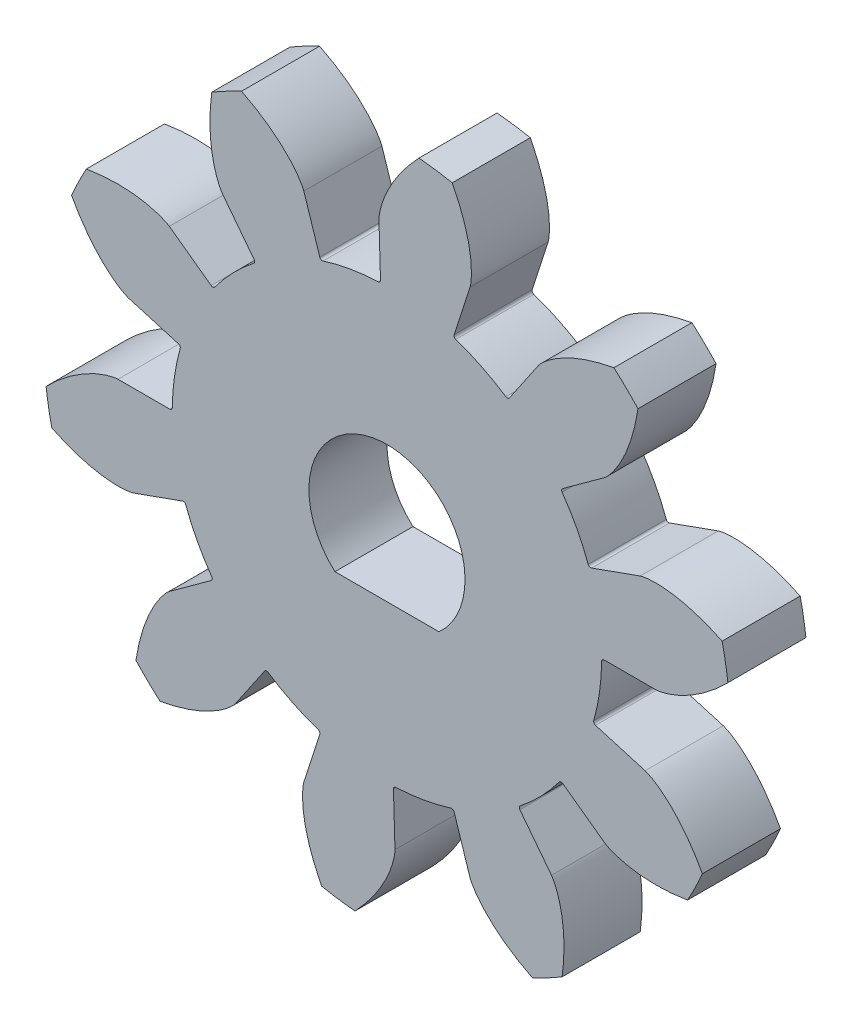
SolidWorks part; units mm, degrees
ref_plane "Front Plane" through (0, 0, 0) normal (0, 0, 1) x (1, 0, 0)
ref_plane "Top Plane" through (0, 0, 0) normal (0, 1, 0) x (1, 0, 0)
ref_plane "Right Plane" through (0, 0, 0) normal (1, 0, 0) x (0, 0, -1)
sketch "Sketch1" plane through (0, 0, 0) normal (0, 0, 1) x (1, 0, 0)
  line L0 (-2, -2.2361) -> (2, -2.2361)
  circle A0 centre (0, 0) radius 13.2013
  arc A1 (2, -2.2361) -> (-2, -2.2361) centre (0, 0) ccw
  dimension "D1" = 26.4026
  dimension "D2" = 6
  dimension "D3" = 4
extrude "Boss-Extrude1" add sketch "Sketch1" along normal blind 3
sketch "Sketch3" plane through (0, 0, 0) normal (0, 0, 1) x (1, 0, 0)
  line L0 (8.2508, 0) -> (10.3377, 0)
  line L1 (9.9225, -2.9001) -> (7.9195, -2.3146)
  line L3 (0, 0) -> (-13.0681, 1.8706) construction
  circle A0 centre (0, 0) radius 11.0011 construction
  circle A1 centre (0, 0) radius 10.3377 construction
  arc A2 (7.9195, -2.3146) -> (8.2508, 0) centre (0, 0) ccw
  circle A3 centre (0, 0) radius 13.2013 construction
  spline S0 degree 4 poles (10.3377, 0) (10.3425, 0.0001) (10.3563, 0.0006) (10.3822, 0.0025) (10.4243, 0.0071) (10.4778, 0.0151) (10.5468, 0.0278) (10.6275, 0.0458) (10.7158, 0.0688) (10.8111, 0.0974) (10.9056, 0.1289) (10.9991, 0.1631) (11.0917, 0.1997) (11.203, 0.247) (11.3352, 0.3079) (11.4879, 0.3849) (11.6587, 0.4791) (11.8299, 0.5825) (11.996, 0.6901) (12.1609, 0.8055) (12.3183, 0.9219) (12.4785, 1.0495) (12.6247, 1.1707) (12.7846, 1.3138) (12.9125, 1.4313) (13.0769, 1.5939) (13.1726, 1.6921) (13.2831, 1.8096) (13.3313, 1.8632) (13.361, 1.8961) knots 0 0 0 0 0 0.005377 0.015084 0.028532 0.04661 0.064855 0.092111 0.119476 0.146842 0.174209 0.201575 0.228941 0.256307 0.307035 0.361767 0.4165 0.471232 0.525964 0.580697 0.635429 0.690161 0.744894 0.799626 0.854358 0.909091 0.954545 1 1 1 1 1 construction
  spline S1 degree 4 poles (10.3377, 0) (10.3425, 0.0001) (10.3563, 0.0006) (10.3822, 0.0025) (10.4243, 0.0071) (10.4778, 0.0151) (10.5468, 0.0278) (10.6275, 0.0458) (10.7158, 0.0688) (10.8111, 0.0974) (10.9056, 0.1289) (10.9991, 0.1631) (11.0917, 0.1997) (11.203, 0.247) (11.3352, 0.3079) (11.4879, 0.3849) (11.6587, 0.4791) (11.8299, 0.5825) (11.996, 0.6901) (12.1609, 0.8055) (12.3183, 0.9219) (12.4785, 1.0495) (12.6247, 1.1707) (12.7846, 1.3138) (12.9125, 1.4313) (13.0413, 1.5586) (13.1034, 1.6215) (13.1349, 1.6539) knots 0 0 0 0 0 0.005377 0.015084 0.028532 0.04661 0.064855 0.092111 0.119476 0.146842 0.174209 0.201575 0.228941 0.256307 0.307035 0.361767 0.4165 0.471232 0.525964 0.580697 0.635429 0.690161 0.744894 0.799626 0.854358 0.909091 0.909091 0.909091 0.909091 0.909091
  spline S2 degree 4 poles (9.9225, -2.9001) (9.9272, -2.9015) (9.9402, -2.9058) (9.9645, -2.915) (10.0037, -2.9312) (10.0529, -2.9538) (10.1155, -2.9854) (10.1879, -3.0253) (10.2662, -3.0722) (10.3497, -3.1263) (10.4315, -3.1831) (10.5117, -3.2422) (10.5903, -3.3033) (10.6838, -3.3799) (10.7937, -3.4754) (10.9186, -3.5922) (11.0561, -3.7306) (11.1915, -3.8778) (11.3207, -4.0277) (11.4466, -4.1847) (11.565, -4.3406) (11.683, -4.508) (11.7893, -4.6654) (11.9027, -4.8475) (11.9925, -4.9962) (12.1046, -5.1984) (12.169, -5.3195) (12.242, -5.4633) (12.2733, -5.5282) (12.2926, -5.5682) knots 0 0 0 0 0 0.005377 0.015084 0.028532 0.04661 0.064855 0.092111 0.119476 0.146842 0.174209 0.201575 0.228941 0.256307 0.307035 0.361767 0.4165 0.471232 0.525964 0.580697 0.635429 0.690161 0.744894 0.799626 0.854358 0.909091 0.954545 1 1 1 1 1 construction
  spline S3 degree 4 poles (9.9225, -2.9001) (9.9272, -2.9015) (9.9402, -2.9058) (9.9645, -2.915) (10.0037, -2.9312) (10.0529, -2.9538) (10.1155, -2.9854) (10.1879, -3.0253) (10.2662, -3.0722) (10.3497, -3.1263) (10.4315, -3.1831) (10.5117, -3.2422) (10.5903, -3.3033) (10.6838, -3.3799) (10.7937, -3.4754) (10.9186, -3.5922) (11.0561, -3.7306) (11.1915, -3.8778) (11.3207, -4.0277) (11.4466, -4.1847) (11.565, -4.3406) (11.683, -4.508) (11.7893, -4.6654) (11.9027, -4.8475) (11.9925, -4.9962) (12.0803, -5.1546) (12.1223, -5.2323) (12.1435, -5.2723) knots 0 0 0 0 0 0.005377 0.015084 0.028532 0.04661 0.064855 0.092111 0.119476 0.146842 0.174209 0.201575 0.228941 0.256307 0.307035 0.361767 0.4165 0.471232 0.525964 0.580697 0.635429 0.690161 0.744894 0.799626 0.854358 0.909091 0.909091 0.909091 0.909091 0.909091
  point P5 (8.2508, 0)
  point P20 (-7.9195, 2.3146)
  dimension "D1" = 22.0022
  dimension "D2" = 20.6753
  dimension "D3" = 16.5017
  dimension "D4" = 8.146
extrude "Cut-Extrude1" cut sketch "Sketch3" against normal through all and the other way through all
fillet "Fillet2" radius 0.1 1 edges at (8.2508, 0, 1.5)
fillet "Fillet4" radius 0.1 1 edges at (7.9195, -2.3146, 1.5)
pattern_circular "CirPattern2" count 10 over 360 about axis through (0, 0, 3) along (0, 0, -1) of "Cut-Extrude1", "Fillet4", "Fillet2"
equation "\"P\" = 0.4545'Diametral Pitch"
equation "\"N\"= 10'Number of teeth"
equation "\"phi\"= 20deg'pressure angle"
equation "\"a\"= 1 / \"P\"'addendum"
equation "\"b\"= 1.25 / \"P\"'dedendum"
equation "\"c\"= \"b\" - \"a\"'clearance"
equation "\"dp\"= \"N\" / \"P\"'pitch circle diameter"
equation "\"db\"= \"dp\" * cos ( \"phi\" )'base circle diameter"
equation "\"D1@Sketch1\"= \"dp\" + 2 * \"a\"'Addendum circle diameter"
equation "\"D1@Sketch3\"= \"dp\"'pitch circle"
equation "\"D2@Sketch3\"= \"db\" 'base circle"
equation "\"D3@Sketch3\" = \"dp\" - 2 * \"b\"'dedendum circle"
equation "\"alpha\"= sqr ( \"dp\" ^ 2 - \"db\" ^ 2 ) / \"db\" * 180 / pi - \"phi\"'alpha (deg)"
equation "\"beta\"= ( 360 / ( 4 * \"N\" ) - \"alpha\" ) * 2"
equation "\"D4@Sketch3\"= 360 / ( 4 * \"N\" ) - \"alpha\""
